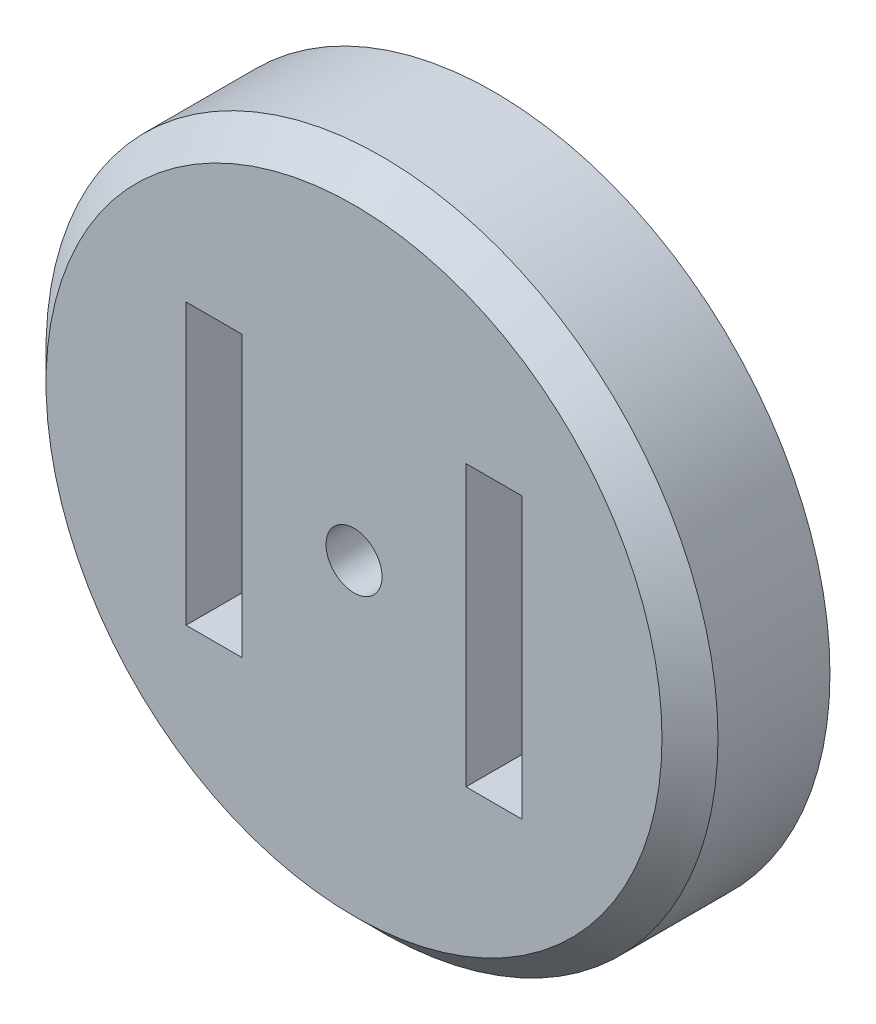
SolidWorks part; units mm, degrees
ref_plane "Plan de face" through (0, 0, 0) normal (0, 0, 1) x (1, 0, 0)
ref_plane "Plan de dessus" through (0, 0, 0) normal (0, 1, 0) x (1, 0, 0)
ref_plane "Plan de droite" through (0, 0, 0) normal (1, 0, 0) x (0, 0, -1)
sketch "Esquisse1" plane through (0, 0, 0) normal (0, 0, 1) x (1, 0, 0)
  circle A0 centre (0, 0) radius 60
  dimension "D1" = 120
extrude "Boss.-Extru.1" add sketch "Esquisse1" along normal blind 25
sketch "Esquisse2" plane through (0, 0, 25) normal (0, 0, 1) x (1, 0, 0)
  line L0 (-20, 0) -> (0, 0) construction
  line L1 (-30, 25) -> (-20, 25)
  line L2 (-30, 25) -> (-30, -25)
  line L3 (-30, -25) -> (-20, -25)
  line L4 (-20, 25) -> (-20, -25)
  line L5 (0, 0) -> (0, 31.5319) construction
  line L6 (20, 25) -> (20, -25)
  line L7 (30, -25) -> (20, -25)
  line L8 (30, 25) -> (30, -25)
  line L9 (30, 25) -> (20, 25)
  dimension "D1" = 10
  dimension "D2" = 40
  dimension "D3" = 50
extrude "Enlèv. mat.-Extru.1" cut sketch "Esquisse2" against normal through all both and the other way through all
chamfer "Chanfrein1" distance 5 angle 45 1 edges at (60, 0, 25)
sketch "Esquisse3" plane through (0, 0, 25) normal (0, 0, 1) x (1, 0, 0)
  circle A0 centre (0, 0) radius 5
  dimension "D1" = 10
extrude "Enlèv. mat.-Extru.2" cut sketch "Esquisse3" against normal through all both and the other way through all
sketch "Esquisse4" plane through (0, 0, 0) normal (0, 0, -1) x (-1, 0, 0)
  circle A0 centre (0, 0) radius 18
  dimension "D1" = 36
extrude "Enlèv. mat.-Extru.3" cut sketch "Esquisse4" against normal blind 4
